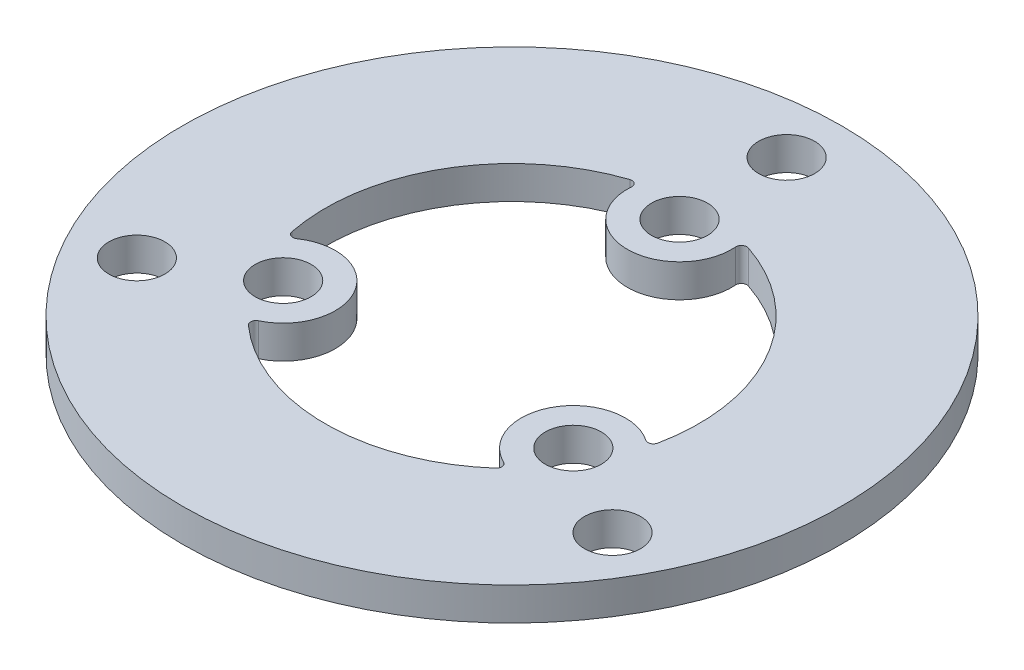
SolidWorks part; units mm, degrees
ref_plane "Front Plane" through (0, 0, 0) normal (0, 0, 1) x (1, 0, 0)
ref_plane "Top Plane" through (0, 0, 0) normal (0, 1, 0) x (1, 0, 0)
ref_plane "Right Plane" through (0, 0, 0) normal (1, 0, 0) x (0, 0, -1)
sketch "Sketch1" plane through (0, 0, 0) normal (0, 1, 0) x (1, 0, 0)
  circle A0 centre (0, 0) radius 30
  circle A1 centre (0, 0) radius 17
  dimension "D1" = 60
  dimension "D2" = 34
extrude "Boss-Extrude1" add sketch "Sketch1" along normal blind 3
sketch "Sketch2" plane through (0, 3, 0) normal (0, 1, 0) x (1, 0, 0)
  circle A0 centre (0, 0) radius 15.25 construction
  circle A1 centre (0, 15.25) radius 2.55
  circle A2 centre (0, 15.25) radius 4.75
  dimension "D1" = 5.1
  dimension "D2" = 30.5
  dimension "D3" = 9.5
extrude "Boss-Extrude2" add sketch "Sketch2" against normal up to surface (3 mm away) up to face at (0, 0, 30)
sketch "Sketch3" plane through (0, 3, 0) normal (0, 1, 0) x (1, 0, 0)
  circle A0 centre (0, 15.25) radius 2.55
  arc A1 (-1.955, 16.8872) -> (1.955, 16.8872) centre (0, 15.25) ccw construction
extrude "Cut-Extrude1" cut sketch "Sketch3" against normal through all
pattern_circular "CirPattern1" count 3 over 360 about axis through (0, 0, 0) along (0, 1, 0) of "Cut-Extrude1", "Boss-Extrude2"
fillet "Fillet1" radius 0.5 6 edges at (11.8596, 1.5, 12.1799) (16.4779, 1.5, 4.1807) (4.6183, 1.5, -16.3607) (-4.6183, 1.5, -16.3607) (-16.4779, 1.5, 4.1807) (-11.8596, 1.5, 12.1799)
sketch "Sketch4" plane through (0, 3, 0) normal (0, 1, 0) x (1, 0, 0)
  circle A0 centre (0, 0) radius 25 construction
  circle A1 centre (0, 25) radius 2.55
  dimension "D1" = 5.1
  dimension "D2" = 50
extrude "Cut-Extrude2" cut sketch "Sketch4" against normal through all
pattern_circular "CirPattern2" count 3 over 360 about axis through (0, 0, 0) along (0, 1, 0) of "Cut-Extrude2"
